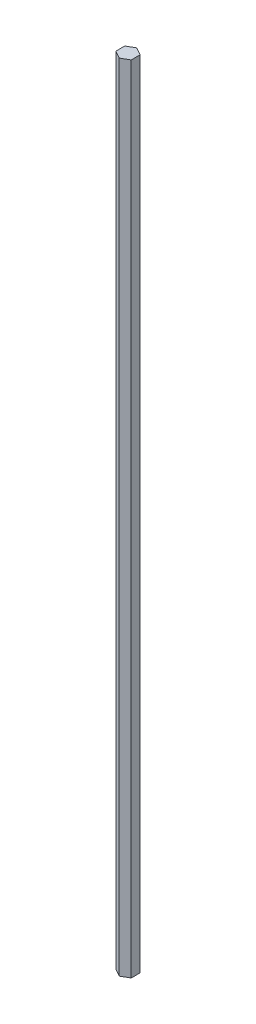
SolidWorks part; units mm, degrees
material "Alloy Steel"
ref_plane "Front Plane" through (0, 0, 0) normal (0, 0, 1) x (1, 0, 0)
ref_plane "Top Plane" through (0, 0, 0) normal (0, 1, 0) x (1, 0, 0)
ref_plane "Right Plane" through (0, 0, 0) normal (1, 0, 0) x (0, 0, -1)
sketch "Sketch1" plane through (0, 0, 0) normal (0, 1, 0) x (1, 0, 0)
  line L1 (0, 7.3323) -> (-6.35, 3.6662)
  line L2 (-6.35, 3.6662) -> (-6.35, -3.6662)
  line L3 (-6.35, -3.6662) -> (0, -7.3323)
  line L4 (0, -7.3323) -> (6.35, -3.6662)
  line L5 (6.35, -3.6662) -> (6.35, 3.6662)
  line L6 (6.35, 3.6662) -> (0, 7.3323)
  circle A0 centre (0, 0) radius 6.35 construction
  dimension "D1" = 12.7
extrude "Boss-Extrude1" add sketch "Sketch1" along normal blind 660.4
